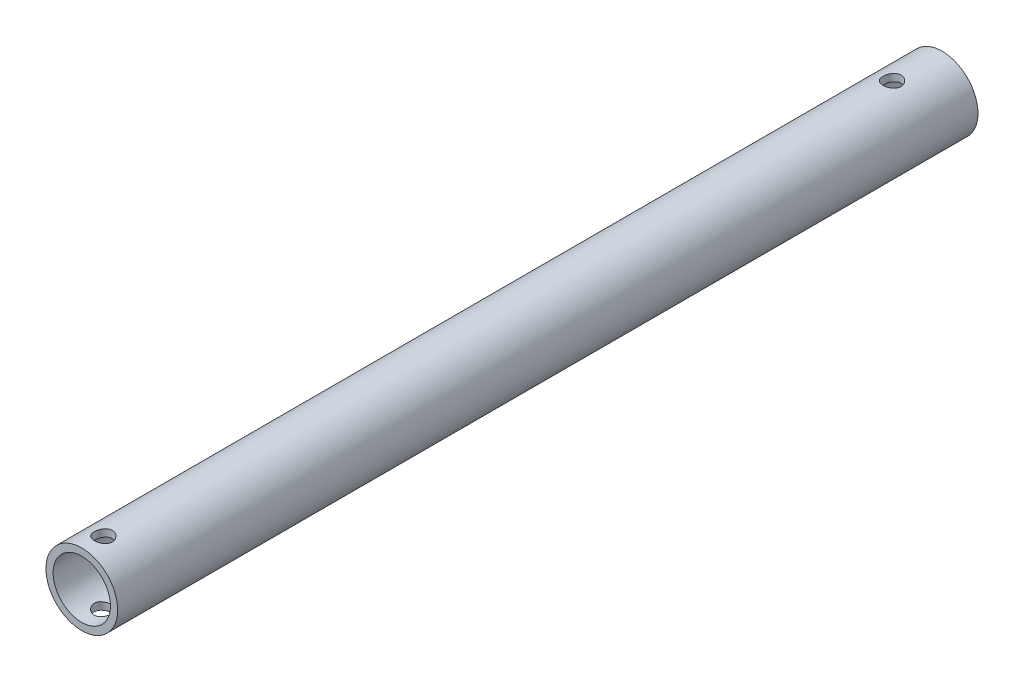
SolidWorks part; units mm, degrees
ref_plane "Front Plane" through (0, 0, 0) normal (0, 0, 1) x (1, 0, 0)
ref_plane "Top Plane" through (0, 0, 0) normal (0, 1, 0) x (1, 0, 0)
ref_plane "Right Plane" through (0, 0, 0) normal (1, 0, 0) x (0, 0, -1)
sketch "Sketch1" plane through (0, 0, 0) normal (0, 0, 1) x (1, 0, 0)
  line L0 (-15.875, 0) -> (15.875, 0) construction
  line L1 (0, -15.875) -> (0, 15.875) construction
  circle A0 centre (0, 0) radius 15.875
  circle A1 centre (0, 0) radius 12.7
  point P4 (0, 0)
  point P9 (0, 0)
  point P10 (12.7, 0)
  dimension "ID" = 25.4
  dimension "OD" = 31.75
  dimension "Wall Thickness" = 3.175
sketch "Sketch2" plane through (0, 0, 0) normal (1, 0, 0) x (0, 0, -1)
  line L0 (457.2, 15.875) -> (-457.2, 15.875) construction
  line L1 (0, 15.875) -> (0, -15.875) construction
  point P3 (-381, 15.875)
  point P4 (0, 15.875)
  point P5 (381, 15.875)
  dimension "D2" = 76.2
  dimension "Length" = 914.4
sketch "Sketch3" plane through (0, 0, 0) normal (0, 0, 1) x (1, 0, 0)
  line L0 (0, -15.875) -> (0, 15.875) construction
  circle A0 centre (0, 0) radius 15.875
  circle A1 centre (0, 0) radius 12.7
  circle A2 centre (0, 0) radius 12.7 construction
extrude "Boss-Extrude1" add sketch "Sketch3" along normal mid plane 914.4
sketch "Sketch4" plane through (0, 0, 457.2) normal (0, 0, 1) x (1, 0, 0)
  circle A0 centre (0, 0) radius 24.6875
extrude "Cut-Extrude1" cut sketch "Sketch4" against normal offset from surface (533.4 mm away) 381 up to face at (15.875, 0, -457.2)
sketch "Sketch5" plane through (0, 0, 0) normal (0, 1, 0) x (1, 0, 0)
  line L0 (-15.875, 76.2) -> (15.875, 76.2) construction
  line L1 (0, 85.725) -> (-15.875, 85.725) construction
  line L2 (-15.875, 457.2) -> (-15.875, 76.2) construction
  line L3 (0, 85.725) -> (15.875, 85.725) construction
  line L4 (15.875, 76.2) -> (15.875, 457.2) construction
  circle A0 centre (0, 85.725) radius 3.9687
  circle A1 centre (0, 434.975) radius 3.9688
  point P12 (0, 0)
  dimension "D1" = 7.9375
  dimension "D3" = 7.9375
  dimension "D2" = 9.525
  dimension "D4" = 358.775
extrude "Cut-Extrude2" cut sketch "Sketch5" against normal through all both and the other way through all
equation "\"D1@Boss-Extrude1\" = \"Length@Sketch2\""
equation "\"D2@Sketch2\"=\"D1@Sketch2\""
